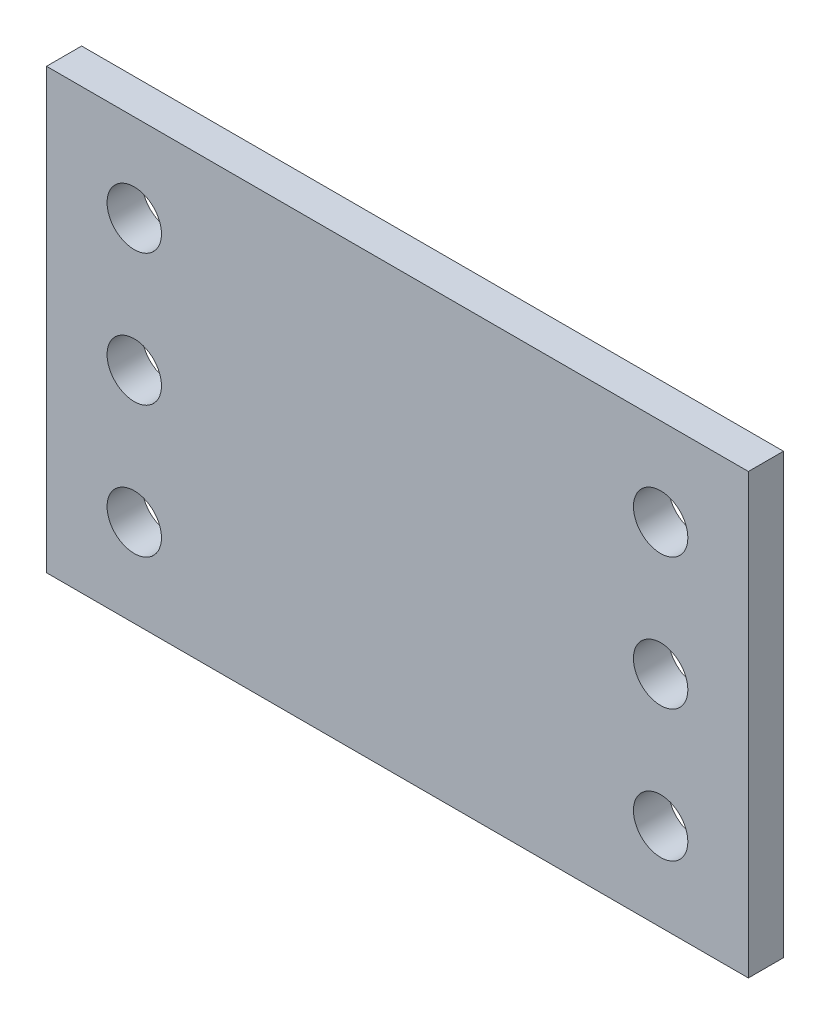
SolidWorks part; units mm, degrees
ref_plane "Front Plane" through (0, 0, 0) normal (0, 0, 1) x (1, 0, 0)
ref_plane "Top Plane" through (0, 0, 0) normal (0, 1, 0) x (1, 0, 0)
ref_plane "Right Plane" through (0, 0, 0) normal (1, 0, 0) x (0, 0, -1)
sketch "Sketch1" plane through (0, 0, 0) normal (0, 0, 1) x (1, 0, 0)
  line L1 (-20, 12.5) -> (20, 12.5)
  line L2 (-20, 12.5) -> (-20, -12.5)
  line L3 (-20, -12.5) -> (20, -12.5)
  line L4 (20, 12.5) -> (20, -12.5)
  line L5 (-20, 12.5) -> (20, -12.5) construction
  line L6 (-20, -12.5) -> (20, 12.5) construction
  point P0 (0, 0)
  dimension "D1" = 40
  dimension "D2" = 25
extrude "Boss-Extrude1" add sketch "Sketch1" along normal blind 2
sketch "Sketch2" plane through (0, 0, 2) normal (0, 0, 1) x (1, 0, 0)
  line L0 (-15, 16.2073) -> (-15, -14.9845) construction
  line L1 (15, 16.2073) -> (15, -14.9845) construction
  line L2 (-20, 12.5) -> (-20, -12.5) construction
  line L3 (0, 14.9951) -> (0, -10.6085) construction
  line L4 (20, 12.5) -> (-20, 12.5) construction
  circle A0 centre (-15, 7.5) radius 1.55
  circle A1 centre (-15, 0) radius 1.55
  circle A2 centre (-15, -7.5) radius 1.55
  circle A3 centre (15, -7.5) radius 1.55
  circle A4 centre (15, 0) radius 1.55
  circle A5 centre (15, 7.5) radius 1.55
  point P6 (-15, 0.6114)
  dimension "D3" = 3.1
  dimension "D1" = 5
  dimension "D2" = 30
  dimension "D4" = 5
  dimension "D5" = 7.5
  dimension "D6" = 7.5
extrude "Cut-Extrude1" cut sketch "Sketch2" against normal up to next
